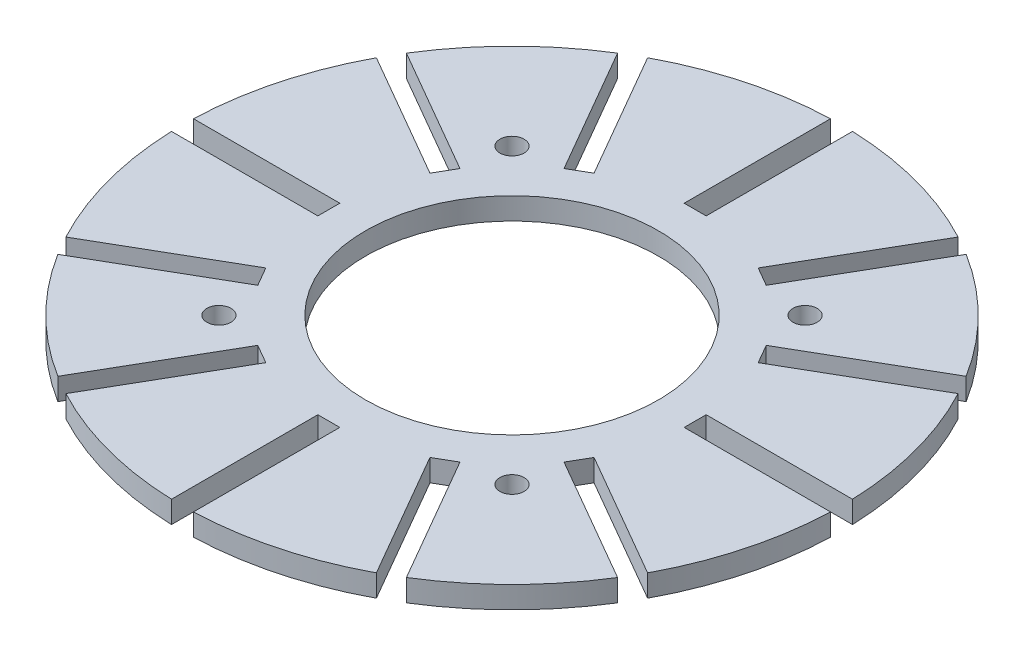
SolidWorks part; units mm, degrees
ref_plane "Front Plane" through (0, 0, 0) normal (0, 0, 1) x (1, 0, 0)
ref_plane "Top Plane" through (0, 0, 0) normal (0, 1, 0) x (1, 0, 0)
ref_plane "Right Plane" through (0, 0, 0) normal (1, 0, 0) x (0, 0, -1)
sketch "Sketch1" plane through (0, 0, 0) normal (0, 1, 0) x (1, 0, 0)
  circle A0 centre (0, 0) radius 45
  circle A1 centre (0, 0) radius 10
  dimension "D1" = 90
  dimension "D2" = 20
extrude "Boss-Extrude1" add sketch "Sketch1" along normal mid plane 3
sketch "Sketch2" plane through (0, 1.5, 0) normal (0, 1, 0) x (1, 0, 0)
  line L1 (20, 20) -> (-20, 20) construction
  line L2 (20, 20) -> (20, -20) construction
  line L3 (20, -20) -> (-20, -20) construction
  line L4 (-20, 20) -> (-20, -20) construction
  line L5 (20, 20) -> (-20, -20) construction
  line L6 (20, -20) -> (-20, 20) construction
  circle A0 centre (-20, -20) radius 1.65
  circle A1 centre (-20, 20) radius 1.65
  circle A2 centre (20, 20) radius 1.65
  circle A3 centre (20, -20) radius 1.65
  point P0 (0, 0)
  dimension "D3" = 3.3
  dimension "D1" = 40
  dimension "D2" = 40
extrude "Cut-Extrude1" cut sketch "Sketch2" against normal blind 10
sketch "Sketch3" plane through (0, 1.5, 0) normal (0, 1, 0) x (1, 0, 0)
  line L0 (0, 0) -> (0, -45) construction
  line L1 (0, 0) -> (0, -45) construction
  line L2 (1.5, -25) -> (1.5, -45)
  line L3 (1.5, -25) -> (-1.5, -25)
  line L4 (1.5, -45) -> (-1.5, -45)
  line L5 (-1.5, -25) -> (-1.5, -45)
  line L6 (1.5, -25) -> (-1.5, -45) construction
  line L7 (1.5, -45) -> (-1.5, -25) construction
  line L8 (-13.799, -20.9006) -> (-23.799, -38.2211)
  line L9 (-11.201, -22.4006) -> (-21.201, -39.7211)
  line L10 (-11.201, -22.4006) -> (-13.799, -20.9006)
  line L11 (-21.201, -39.7211) -> (-23.799, -38.2211)
  line L12 (-22.4006, -11.201) -> (-39.7211, -21.201)
  line L13 (-20.9006, -13.799) -> (-38.2211, -23.799)
  line L14 (-20.9006, -13.799) -> (-22.4006, -11.201)
  line L15 (-38.2211, -23.799) -> (-39.7211, -21.201)
  line L16 (-25, 1.5) -> (-45, 1.5)
  line L17 (-25, -1.5) -> (-45, -1.5)
  line L18 (-25, -1.5) -> (-25, 1.5)
  line L19 (-45, -1.5) -> (-45, 1.5)
  line L20 (-20.9006, 13.799) -> (-38.2211, 23.799)
  line L21 (-22.4006, 11.201) -> (-39.7211, 21.201)
  line L22 (-22.4006, 11.201) -> (-20.9006, 13.799)
  line L23 (-39.7211, 21.201) -> (-38.2211, 23.799)
  line L24 (-11.201, 22.4006) -> (-21.201, 39.7211)
  line L25 (-13.799, 20.9006) -> (-23.799, 38.2211)
  line L26 (-13.799, 20.9006) -> (-11.201, 22.4006)
  line L27 (-23.799, 38.2211) -> (-21.201, 39.7211)
  line L28 (1.5, 25) -> (1.5, 45)
  line L29 (-1.5, 25) -> (-1.5, 45)
  line L30 (-1.5, 25) -> (1.5, 25)
  line L31 (-1.5, 45) -> (1.5, 45)
  line L32 (13.799, 20.9006) -> (23.799, 38.2211)
  line L33 (11.201, 22.4006) -> (21.201, 39.7211)
  line L34 (11.201, 22.4006) -> (13.799, 20.9006)
  line L35 (21.201, 39.7211) -> (23.799, 38.2211)
  line L36 (22.4006, 11.201) -> (39.7211, 21.201)
  line L37 (20.9006, 13.799) -> (38.2211, 23.799)
  line L38 (20.9006, 13.799) -> (22.4006, 11.201)
  line L39 (38.2211, 23.799) -> (39.7211, 21.201)
  line L40 (25, -1.5) -> (45, -1.5)
  line L41 (25, 1.5) -> (45, 1.5)
  line L42 (25, 1.5) -> (25, -1.5)
  line L43 (45, 1.5) -> (45, -1.5)
  line L44 (20.9006, -13.799) -> (38.2211, -23.799)
  line L45 (22.4006, -11.201) -> (39.7211, -21.201)
  line L46 (22.4006, -11.201) -> (20.9006, -13.799)
  line L47 (39.7211, -21.201) -> (38.2211, -23.799)
  line L48 (11.201, -22.4006) -> (21.201, -39.7211)
  line L49 (13.799, -20.9006) -> (23.799, -38.2211)
  line L50 (13.799, -20.9006) -> (11.201, -22.4006)
  line L51 (23.799, -38.2211) -> (21.201, -39.7211)
  circle A0 centre (0, 0) radius 45 construction
  point P7 (0, -35)
  point P58 (0, 0)
  dimension "D1" = 3
  dimension "D2" = 20
  dimension "D3" = 0
  dimension "D4" = 12
extrude "Cut-Extrude2" cut sketch "Sketch3" against normal blind 10
sketch "Sketch4" plane through (0, 1.5, 0) normal (0, 1, 0) x (1, 0, 0)
  circle A0 centre (0, 0) radius 20
  dimension "D1" = 40
extrude "Cut-Extrude3" cut sketch "Sketch4" against normal blind 10
